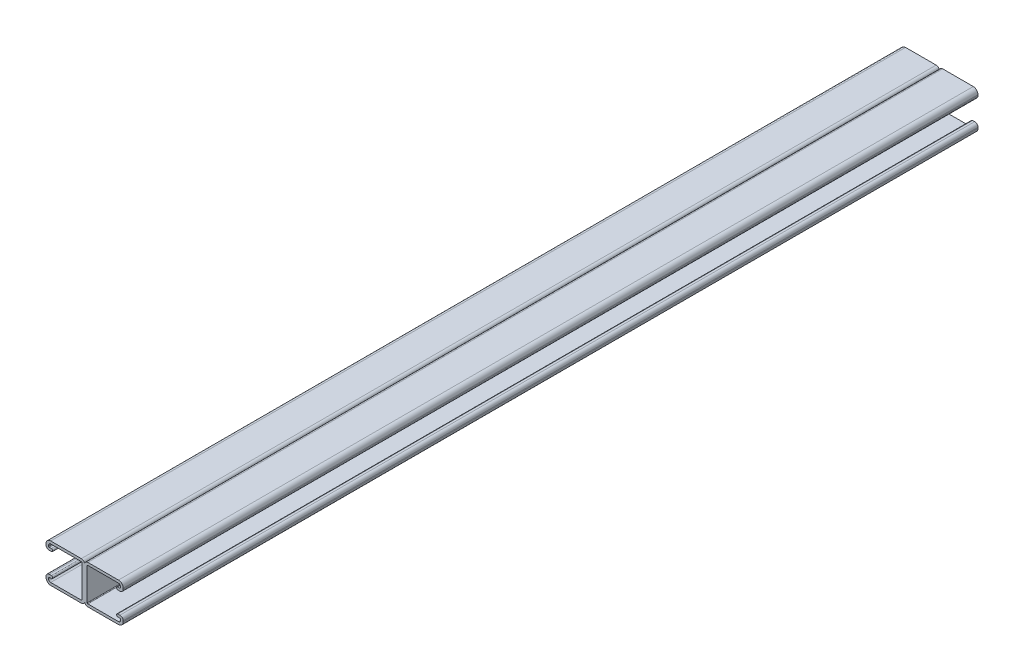
SolidWorks part; units mm, degrees
ref_plane "Front Plane" through (0, 0, 0) normal (0, 0, 1) x (1, 0, 0)
ref_plane "Top Plane" through (0, 0, 0) normal (0, 1, 0) x (1, 0, 0)
ref_plane "Right Plane" through (0, 0, 0) normal (1, 0, 0) x (0, 0, -1)
sketch "Sketch1" plane through (0, 0, 0) normal (0, 0, 1) x (1, 0, 0)
  line L0 (0, 0) -> (-41.275, 0) construction
  line L3 (-41.275, 20.6375) -> (0, 20.6375) construction
  line L4 (-41.275, 20.6375) -> (-41.275, -20.6375) construction
  line L5 (-41.275, -20.6375) -> (0, -20.6375) construction
  line L6 (0, 20.6375) -> (0, -20.6375) construction
  line L7 (-36.2267, 20.6375) -> (-3.4607, 20.6375)
  line L8 (0, 17.1767) -> (0, -17.1767)
  line L9 (-2.794, -17.1767) -> (-2.794, 17.1767)
  line L10 (-3.4608, 17.8435) -> (-36.2267, 17.8435)
  line L11 (-41.275, 15.5892) -> (-41.275, 14.5732)
  line L12 (-37.8142, 11.1125) -> (-35.5346, 11.1125)
  line L14 (-35.5346, 13.9065) -> (-37.8142, 13.9065)
  line L15 (-38.481, 14.5732) -> (-38.481, 15.5892)
  line L16 (-38.481, -14.5733) -> (-38.481, -15.5893)
  line L17 (-35.5346, -13.9065) -> (-37.8142, -13.9065)
  line L18 (-37.8142, -11.1125) -> (-35.5346, -11.1125)
  line L19 (-41.275, -15.5893) -> (-41.275, -14.5733)
  line L20 (-3.4607, -17.8435) -> (-36.2267, -17.8435)
  line L21 (-36.2267, -20.6375) -> (-3.4607, -20.6375)
  line L22 (-2.794, -20.6375) -> (-2.794, 20.6375) construction
  arc A1 (0, 17.1767) -> (-3.4607, 20.6375) centre (-3.4607, 17.1767) ccw
  arc A2 (-2.794, 17.1767) -> (-3.4608, 17.8435) centre (-3.4607, 17.1767) ccw
  arc A4 (-36.2267, 20.6375) -> (-41.275, 15.5892) centre (-36.2267, 15.5892) ccw
  arc A5 (-41.275, 14.5732) -> (-37.8142, 11.1125) centre (-37.8142, 14.5732) ccw
  arc A6 (-35.5346, 11.1125) -> (-35.5346, 13.9065) centre (-35.5346, 12.5095) ccw
  arc A7 (-37.8142, 13.9065) -> (-38.481, 14.5732) centre (-37.8142, 14.5732) cw
  arc A8 (-38.481, 15.5892) -> (-36.2267, 17.8435) centre (-36.2267, 15.5892) cw
  arc A9 (-38.481, -15.5893) -> (-36.2267, -17.8435) centre (-36.2267, -15.5893) ccw
  arc A10 (-37.8142, -13.9065) -> (-38.481, -14.5733) centre (-37.8142, -14.5733) ccw
  arc A11 (-35.5346, -11.1125) -> (-35.5346, -13.9065) centre (-35.5346, -12.5095) cw
  arc A12 (-41.275, -14.5733) -> (-37.8142, -11.1125) centre (-37.8142, -14.5733) cw
  arc A13 (-36.2267, -20.6375) -> (-41.275, -15.5893) centre (-36.2267, -15.5893) cw
  arc A14 (-2.794, -17.1767) -> (-3.4607, -17.8435) centre (-3.4607, -17.1767) cw
  arc A15 (0, -17.1767) -> (-3.4607, -20.6375) centre (-3.4607, -17.1767) cw
  point P24 (0, 20.6375)
  point P65 (-2.794, 0)
  dimension "D1" = 3.4608
  dimension "D2" = 5.0482
  dimension "D3" = 3.4608
  dimension "Ht." = 41.275
  dimension "Wd." = 41.275
  dimension "Thk." = 2.794
  dimension "D4" = 9.525
  dimension "D5" = 7.1374
extrude "Boss-Extrude1" add sketch "Sketch1" against normal blind 914.4
sketch "Sketch3" plane through (0, 0, 0) normal (1, 0, 0) x (0, 0, -1)
  line L0 (0, 0) -> (914.4, 0) construction
  point P2 (101.6, 0)
  point P3 (812.8, 0)
  dimension "D1" = 101.6
  dimension "D2" = 101.6
  dimension "D3" = 914.4
mirror "Mirror1" about plane through (0, 17.1767, -914.4) normal (1, 0, 0) of bodies 114
combine bodies "Combine1" operation type add bodies to combine 114 117
equation "\"D3@Sketch3\" = \"Lg.@Boss-Extrude1\""
